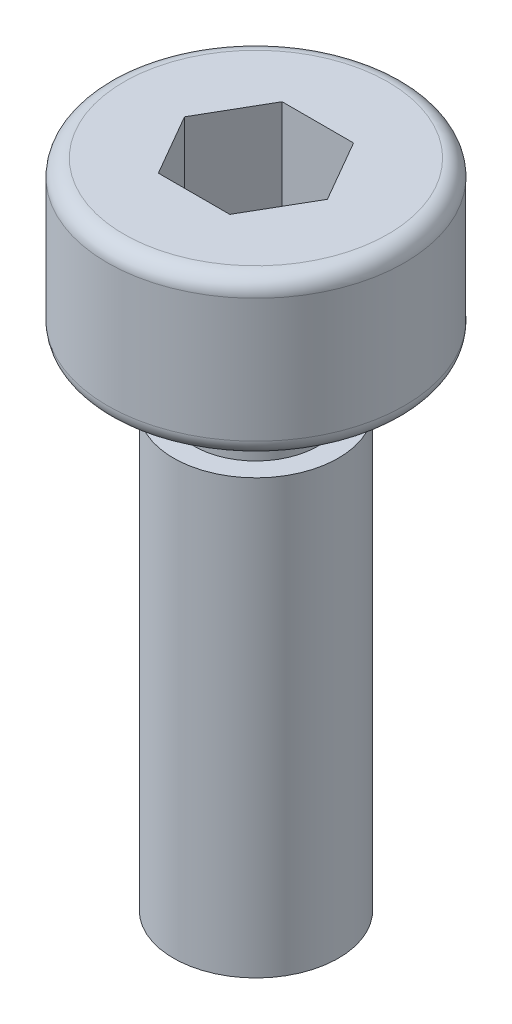
SolidWorks part; units mm, degrees
material "AISI 304"
ref_plane "前视基准面" through (0, 0, 0) normal (0, 0, 1) x (1, 0, 0)
ref_plane "上视基准面" through (0, 0, 0) normal (0, 1, 0) x (1, 0, 0)
ref_plane "右视基准面" through (0, 0, 0) normal (1, 0, 0) x (0, 0, -1)
sketch "草图1" plane through (0, 0, 0) normal (0, 0, 1) x (1, 0, 0)
  line L0 (0, 0) -> (0, 15.8) construction
  line L1 (0, 15.8) -> (-3.2, 15.8)
  line L2 (-3.6, 15.4) -> (-3.6, 12.4)
  line L3 (-3.2, 12) -> (-1.5, 12)
  line L4 (-1.5, 12) -> (-1.5, 10.5)
  line L5 (-1.5, 10.5) -> (-2, 10.5)
  line L6 (-2, 10.5) -> (-2, 0)
  line L7 (-2, 0) -> (0, 0)
  line L8 (0, 0) -> (0, 15.8)
  arc A0 (-3.6, 12.4) -> (-3.2, 12) centre (-3.2, 12.4) ccw
  arc A1 (-3.2, 15.8) -> (-3.6, 15.4) centre (-3.2, 15.4) ccw
  point P11 (-3.6, 12)
  point P14 (-3.6, 15.8)
  dimension "D7" = 0.4
  dimension "D1" = 12
  dimension "D2" = 3.8
  dimension "D3" = 7.2
  dimension "D4" = 4
  dimension "D5" = 1.5
  dimension "D6" = 0.5
revolve "旋转1" add sketch "草图1" angle 360 about L0
cosmetic thread "装饰螺纹线1" parameters "D2"=3.22
sketch "草图2" plane through (0, 15.8, 0) normal (0, 1, 0) x (1, 0, 0)
  line L1 (-0.866, 1.5) -> (-1.7321, 0)
  line L2 (-1.7321, 0) -> (-0.866, -1.5)
  line L3 (-0.866, -1.5) -> (0.866, -1.5)
  line L4 (0.866, -1.5) -> (1.7321, 0)
  line L5 (1.7321, 0) -> (0.866, 1.5)
  line L6 (0.866, 1.5) -> (-0.866, 1.5)
  circle A0 centre (0, 0) radius 1.5 construction
  dimension "D1" = 3
extrude "切除-拉伸1" cut sketch "草图2" against normal blind 2.8
